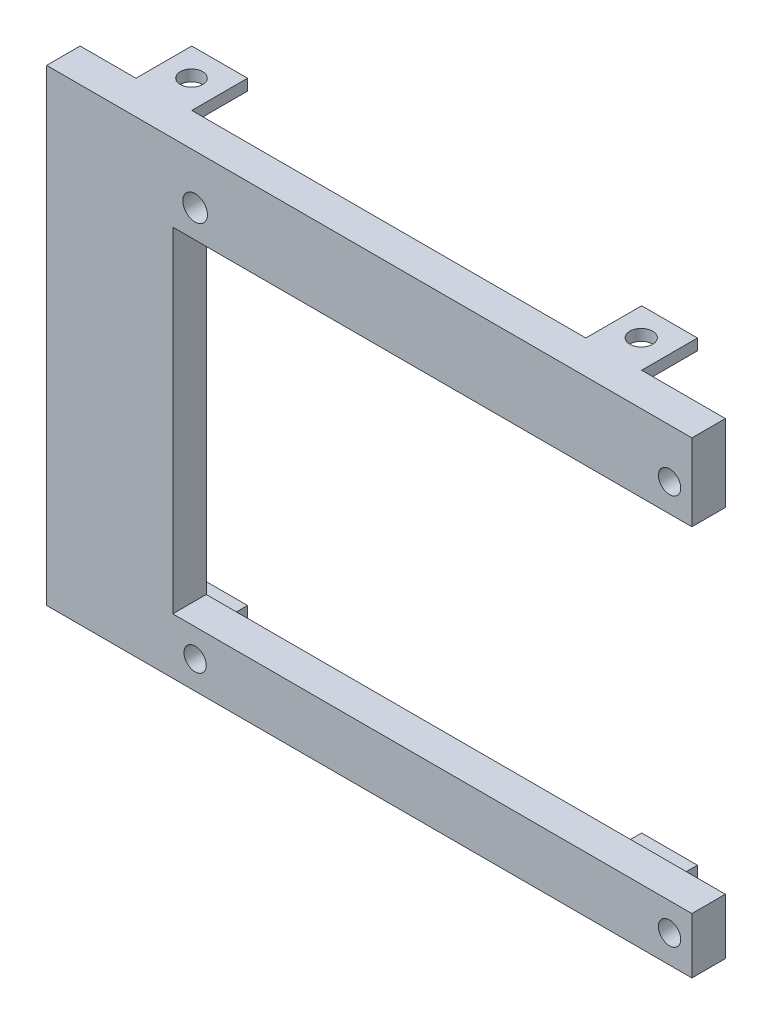
SolidWorks part; units mm, degrees
ref_plane "前视基准面" through (0, 0, 0) normal (0, 0, 1) x (1, 0, 0)
ref_plane "上视基准面" through (0, 0, 0) normal (0, 1, 0) x (1, 0, 0)
ref_plane "右视基准面" through (0, 0, 0) normal (1, 0, 0) x (0, 0, -1)
sketch "草图1" plane through (0, 0, 0) normal (0, 0, 1) x (1, 0, 0)
  line L1 (-520.9068, 348.1867) -> (-405.3068, 348.1867) construction
  line L9 (-520.9068, 348.1867) -> (-405.3068, 348.1867)
  line L10 (-520.9068, 348.1867) -> (-520.9068, 264.3867)
  line L11 (-520.9068, 264.3867) -> (-405.3068, 264.3867)
  line L12 (-405.3068, 348.1867) -> (-405.3068, 264.3867)
  line L13 (-520.9068, 348.1867) -> (-520.9068, 264.3867) construction
  line L15 (-498.3068, 334.3867) -> (-405.3068, 334.3867)
  line L16 (-498.3068, 334.3867) -> (-498.3068, 274.3867)
  line L17 (-498.3068, 274.3867) -> (-405.3068, 274.3867)
  line L18 (-405.3068, 334.3867) -> (-405.3068, 274.3867)
extrude "凸台-拉伸1" add sketch "草图1" against normal up to surface (6 mm away) contours L10 L11 L12 L9 | L16 L17 L18 L15
sketch "草图2" plane through (0, 0, -6) normal (0, 0, -1) x (-1, 0, 0)
  line L0 (520.9068, 348.1867) -> (405.3068, 348.1867) construction
  line L1 (500.9068, 348.1867) -> (510.9068, 348.1867)
  line L2 (500.9068, 348.1867) -> (500.9068, 346.1867)
  line L3 (500.9068, 346.1867) -> (510.9068, 346.1867)
  line L4 (510.9068, 348.1867) -> (510.9068, 346.1867)
  line L5 (520.9068, 348.1867) -> (520.9068, 264.3867) construction
  line L6 (500.9068, 266.3867) -> (510.9068, 266.3867)
  line L7 (500.9068, 266.3867) -> (500.9068, 264.3867)
  line L8 (500.9068, 264.3867) -> (510.9068, 264.3867)
  line L9 (510.9068, 266.3867) -> (510.9068, 264.3867)
  line L10 (520.9068, 264.3867) -> (405.3068, 264.3867) construction
  dimension "D1" = 10
  dimension "D2" = 2
  dimension "D3" = 10
  dimension "D4" = 10
  dimension "D5" = 2
extrude "凸台-拉伸2" add sketch "草图2" along normal blind 10
sketch "草图3" plane through (0, 0, -6) normal (0, 0, -1) x (-1, 0, 0)
  line L0 (500.9068, 348.1867) -> (405.3068, 348.1867) construction
  line L1 (420.3068, 348.1867) -> (430.3068, 348.1867)
  line L2 (420.3068, 348.1867) -> (420.3068, 346.1867)
  line L3 (420.3068, 346.1867) -> (430.3068, 346.1867)
  line L4 (430.3068, 348.1867) -> (430.3068, 346.1867)
  line L5 (405.3068, 348.1867) -> (405.3068, 334.3867) construction
  line L11 (500.9068, 264.3867) -> (405.3068, 264.3867) construction
  line L12 (420.3068, 266.3867) -> (430.3068, 266.3867)
  line L13 (420.3068, 266.3867) -> (420.3068, 264.3867)
  line L14 (420.3068, 264.3867) -> (430.3068, 264.3867)
  line L15 (430.3068, 266.3867) -> (430.3068, 264.3867)
  dimension "D1" = 15
  dimension "D2" = 10
  dimension "D3" = 2
  dimension "D4" = 2
extrude "凸台-拉伸3" add sketch "草图3" along normal blind 10
sketch "草图4" plane through (0, 348.1867, 0) normal (0, 1, 0) x (1, 0, 0)
  circle A0 centre (-425.3802, 11) radius 2.04
  circle A1 centre (-505.9528, 11) radius 2
extrude "切除-拉伸1" cut sketch "草图4" against normal blind 9
sketch "草图5" plane through (0, 264.3867, 0) normal (0, -1, 0) x (1, 0, 0)
  circle A0 centre (-505.9528, -11) radius 2
  circle A1 centre (-425.3802, -11) radius 2
extrude "切除-拉伸2" cut sketch "草图5" against normal blind 9
sketch "草图7" plane through (0, 0, 0) normal (0, 0, 1) x (1, 0, 0)
  circle A0 centre (-494.3068, 339.3867) radius 2.2069
  circle A1 centre (-409.3068, 339.3867) radius 2
  circle A2 centre (-409.3068, 269.3867) radius 2.0048
  circle A3 centre (-494.3068, 269.3867) radius 2
extrude "切除-拉伸3" cut sketch "草图7" against normal blind 9
